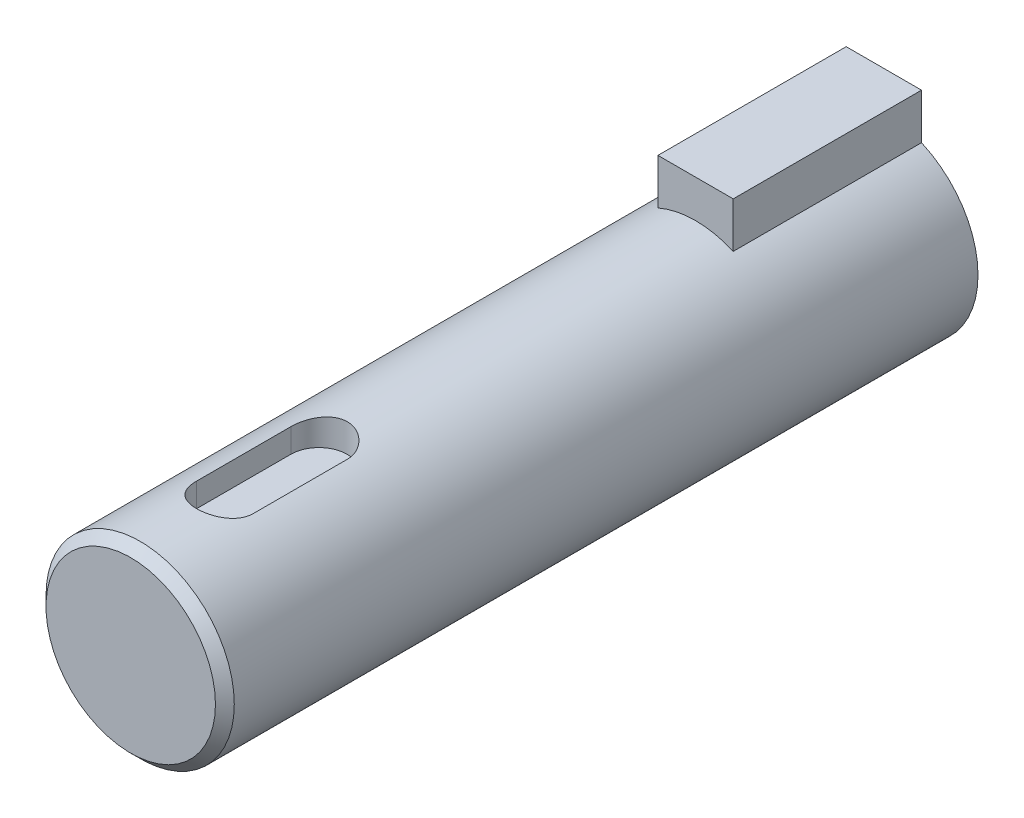
SolidWorks part; units mm, degrees
ref_plane "Front Plane" through (0, 0, 0) normal (0, 0, 1) x (1, 0, 0)
ref_plane "Top Plane" through (0, 0, 0) normal (0, 1, 0) x (1, 0, 0)
ref_plane "Right Plane" through (0, 0, 0) normal (1, 0, 0) x (0, 0, -1)
sketch "Sketch1" plane through (0, 0, 0) normal (0, 0, 1) x (1, 0, 0)
  line L0 (0, 0) -> (0, 6.5692) construction
  line L3 (-2, 4.5826) -> (-2, 7)
  line L4 (-2, 7) -> (2, 7)
  line L5 (2, 4.5826) -> (2, 7)
  line L6 (-0.1812, 4.9967) -> (2, 7) construction
  line L7 (-2, 7) -> (0.1812, 4.9967) construction
  arc A0 (-2, 4.5826) -> (2, 4.5826) centre (0, 0) ccw
  arc A1 (0.1812, 4.9967) -> (-0.1812, 4.9967) centre (0, 0) ccw
  point P3 (0, 5.1632)
  dimension "D1" = 10
  dimension "D2" = 4
  dimension "D3" = 7
extrude "Boss-Extrude1" add sketch "Sketch1" along normal blind 10
sketch "Sketch2" plane through (0, 0, 10) normal (0, 0, 1) x (1, 0, 0)
  circle A0 centre (0, 0) radius 5
extrude "Boss-Extrude2" add sketch "Sketch2" along normal blind 30
sketch "Sketch3" plane through (0, 0, 0) normal (0, 1, 0) x (1, 0, 0)
  line L0 (0, -40) -> (0, -18.1859) construction
  line L1 (-5, -40) -> (5, -40) construction
  line L2 (0, -35) -> (0, -30) construction
  line L3 (-1.5, -35) -> (-1.5, -30)
  line L4 (1.5, -35) -> (1.5, -30)
  arc A0 (-1.5, -35) -> (1.5, -35) centre (0, -35) ccw
  arc A1 (1.5, -30) -> (-1.5, -30) centre (0, -30) ccw
  point P7 (0, -32.5)
  dimension "D1" = 3
  dimension "D2" = 5
  dimension "D3" = 5
extrude "Cut-Extrude1" cut sketch "Sketch3" along normal through all from offset 3.5
chamfer "Chamfer1" distance 0.5 angle 45 1 edges at (5, 0, 40)
